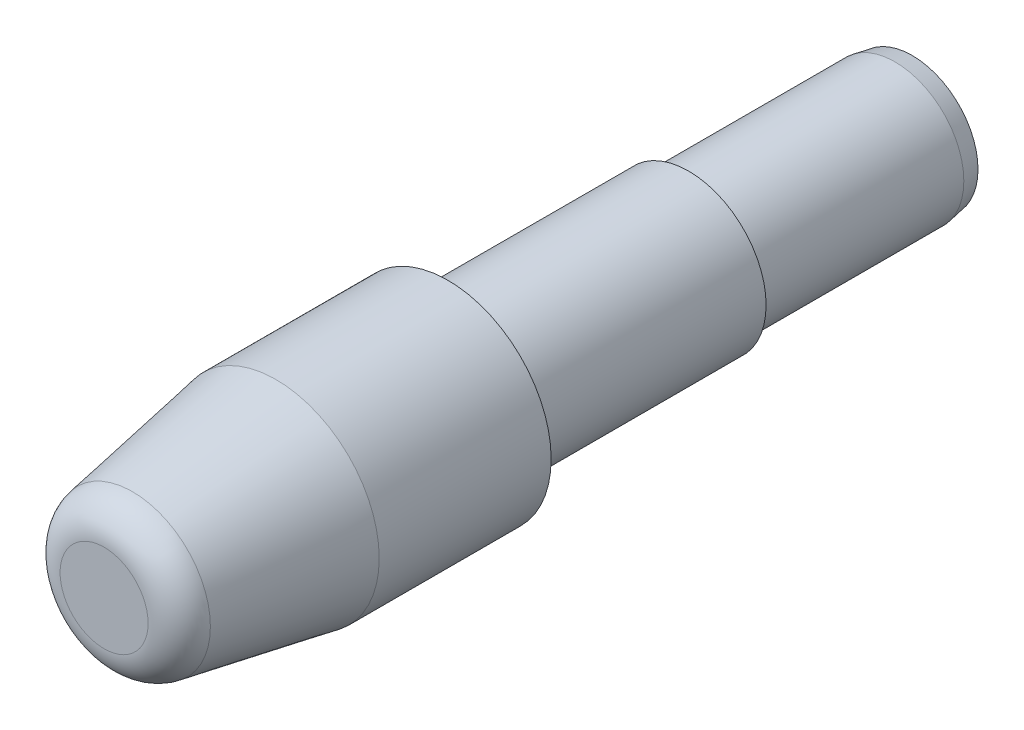
SolidWorks part; units mm, degrees
ref_plane "Alzado" through (0, 0, 0) normal (0, 0, 1) x (1, 0, 0)
ref_plane "Planta" through (0, 0, 0) normal (0, 1, 0) x (1, 0, 0)
ref_plane "Vista lateral" through (0, 0, 0) normal (1, 0, 0) x (0, 0, -1)
sketch "Croquis1" plane through (0, 0, 0) normal (0, 0, 1) x (1, 0, 0)
  circle A0 centre (0, 0) radius 6
  dimension "D1" = 12
extrude "Saliente-Extruir1" add sketch "Croquis1" along normal blind 10
sketch "Croquis2" plane through (0, 0, 10) normal (0, 0, 1) x (1, 0, 0)
  circle A0 centre (0, 0) radius 6
extrude "Saliente-Extruir2" add sketch "Croquis2" along normal blind 10
chamfer "Chaflán1" distance 10 angle 10 1 edges at (6, 0, 20)
fillet "Redondeo1" radius 2 1 edges at (4.2367, 0, 20)
sketch "Croquis3" plane through (0, 0, 0) normal (0, 0, -1) x (-1, 0, 0)
  circle A0 centre (0, 0) radius 4.5
  dimension "D1" = 9
extrude "Saliente-Extruir3" add sketch "Croquis3" along normal blind 14
sketch "Croquis4" plane through (0, 0, -14) normal (0, 0, -1) x (-1, 0, 0)
  circle A0 centre (0, 0) radius 4
  dimension "D1" = 8
extrude "Saliente-Extruir4" add sketch "Croquis4" along normal blind 13
chamfer "Chaflán2" distance 1 angle 10 1 edges at (-4, 0, -27)
